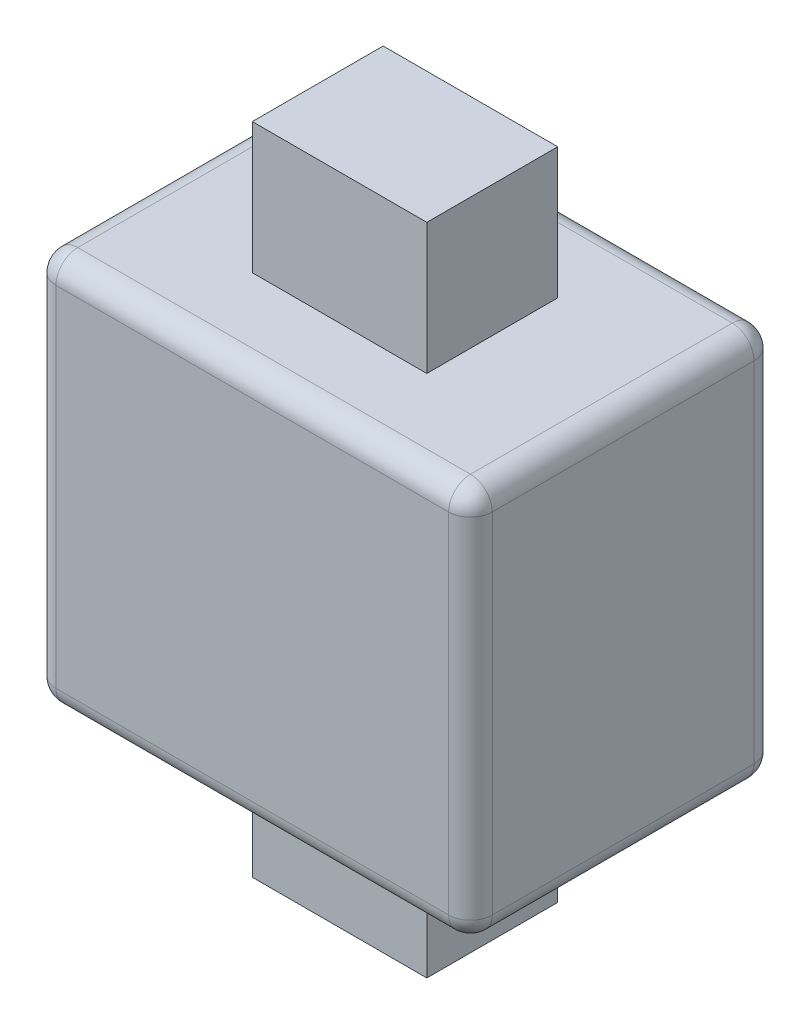
SolidWorks part; units mm, degrees
ref_plane "Front Plane" through (0, 0, 0) normal (0, 0, 1) x (1, 0, 0)
ref_plane "Top Plane" through (0, 0, 0) normal (0, 1, 0) x (1, 0, 0)
ref_plane "Right Plane" through (0, 0, 0) normal (1, 0, 0) x (0, 0, -1)
sketch "Sketch1" plane through (0, 0, 0) normal (0, 0, 1) x (1, 0, 0)
  line L1 (-2.5, 2.25) -> (2.5, 2.25)
  line L2 (-2.5, 2.25) -> (-2.5, -2.25)
  line L3 (-2.5, -2.25) -> (2.5, -2.25)
  line L4 (2.5, 2.25) -> (2.5, -2.25)
  line L5 (-2.5, 2.25) -> (2.5, -2.25) construction
  line L6 (-2.5, -2.25) -> (2.5, 2.25) construction
  point P0 (0, 0)
  dimension "D1" = 5
  dimension "D2" = 4.5
extrude "Boss-Extrude1" add sketch "Sketch1" along normal blind 3.5
sketch "Sketch2" plane through (0, 2.25, 0) normal (0, 1, 0) x (1, 0, 0)
  line L0 (2.5, 0) -> (-2.5, -3.5)
  line L2 (1, -2.5) -> (-1, -2.5)
  line L3 (1, -2.5) -> (1, -1)
  line L4 (1, -1) -> (-1, -1)
  line L5 (-1, -2.5) -> (-1, -1)
  line L6 (1, -2.5) -> (-1, -1) construction
  line L7 (1, -1) -> (-1, -2.5) construction
  point P4 (0, -1.75)
  dimension "D1" = 1.5
  dimension "D2" = 2
extrude "Boss-Extrude2" add sketch "Sketch2" along normal blind 1.5 contours L5 L0 L3 L4 | L5 L2 L3 L0
sketch "Sketch3" plane through (0, -2.25, 0) normal (0, -1, 0) x (-1, 0, 0)
  line L0 (-2.5, -3.5) -> (2.5, 0)
  line L2 (1, -2.5) -> (-1, -2.5)
  line L3 (1, -2.5) -> (1, -1)
  line L4 (1, -1) -> (-1, -1)
  line L5 (-1, -2.5) -> (-1, -1)
  line L6 (1, -2.5) -> (-1, -1) construction
  line L7 (1, -1) -> (-1, -2.5) construction
  point P4 (0, -1.75)
  dimension "D1" = 1.5
  dimension "D2" = 2
extrude "Boss-Extrude3" add sketch "Sketch3" along normal blind 1.5 contours L5 L0 L3 L4 | L5 L2 L3 L0
fillet "Fillet1" radius 0.25 12 edges at (-2.5, -2.25, 1.75) (0, -2.25, 3.5) (2.5, -2.25, 1.75) (0, -2.25, 0) (2.5, 0, 0) (-2.5, 0, 0) (2.5, 0, 3.5) (-2.5, 0, 3.5) (0, 2.25, 0) (-2.5, 2.25, 1.75) (2.5, 2.25, 1.75) (0, 2.25, 3.5)
